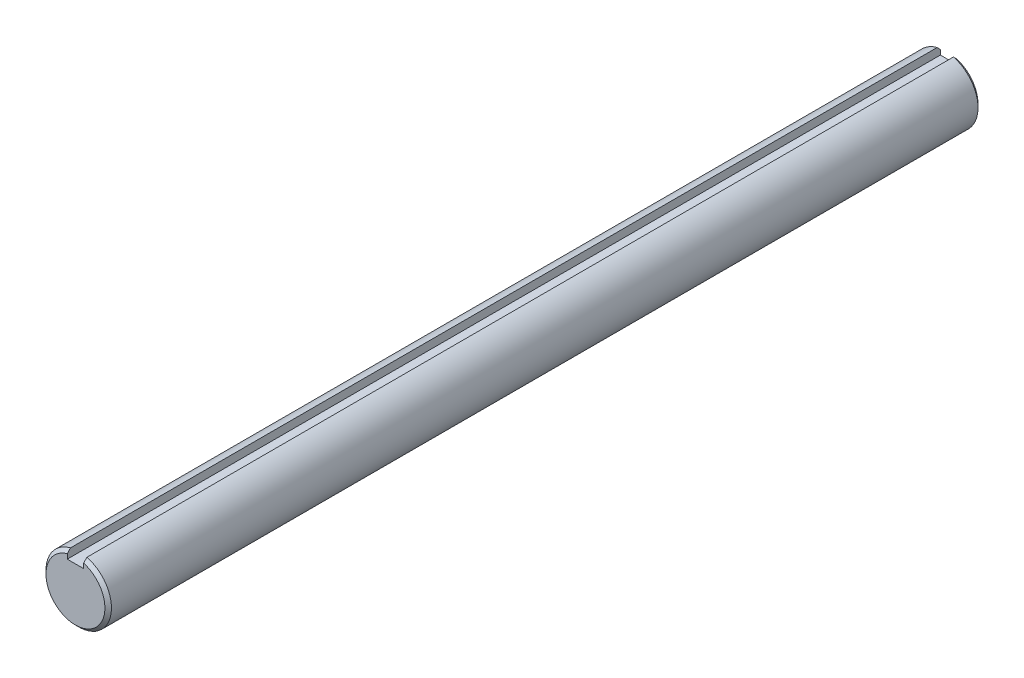
SolidWorks part; units mm, degrees
ref_plane "Front Plane" through (0, 0, 0) normal (0, 0, 1) x (1, 0, 0)
ref_plane "Top Plane" through (0, 0, 0) normal (0, 1, 0) x (1, 0, 0)
ref_plane "Right Plane" through (0, 0, 0) normal (1, 0, 0) x (0, 0, -1)
sketch "Sketch1" plane through (0, 0, 0) normal (0, 0, 1) x (1, 0, 0)
  line L0 (-6.7352, -6.7352) -> (-1.1225, -1.1225) construction
  line L1 (3.4925, 0) -> (-3.4925, 0) construction
  line L2 (0, 0) -> (0, 9.525) construction
  line L4 (-2.3813, 9.525) -> (2.3813, 9.525) construction
  line L5 (-2.3813, 9.525) -> (-2.3813, 6.8413) construction
  line L6 (-2.3813, 6.8413) -> (2.3813, 6.8413) construction
  line L7 (2.3813, 9.525) -> (2.3813, 6.8413) construction
  line L8 (-2.3813, 9.525) -> (2.3813, 6.8413) construction
  line L9 (-2.3813, 6.8413) -> (2.3813, 9.525) construction
  circle A0 centre (0, 0) radius 1.5875 construction
  circle A1 centre (0, 0) radius 9.525 construction
  point P6 (0, 8.1831)
  point P16 (-2.3813, 9.2225)
  dimension "Diameter" = 19.05
  dimension "Thread Dia" = 3.175
  dimension "D1" = 45
  dimension "Keyway Wd" = 4.7625
  dimension "Keyway Ht" = 2.3813
sketch "Sketch2" plane through (0, 0, 0) normal (1, 0, 0) x (0, 0, -1)
  line L0 (-127, -9.525) -> (127, -9.525) construction
  line L1 (0, 9.525) -> (0, -9.525) construction
  line L2 (0, 9.525) -> (0, -9.525) construction
  point P3 (88.9, -9.525)
  point P4 (-88.9, -9.525)
  dimension "Length" = 254
  dimension "D1" = 38.1
  dimension "D2" = 38.1
sketch "Sketch3" plane through (0, 0, 0) normal (0, 0, 1) x (1, 0, 0)
  circle A1 centre (0, 0) radius 9.525 construction
  circle A3 centre (0, 0) radius 9.525
extrude "Boss-Extrude2" add sketch "Sketch3" along normal up to vertex (127 mm away) and the other way up to vertex (127 mm away) up to point (0, -9.525, 127) other way up to point (0, -9.525, -127)
sketch "Sketch10" plane through (0, 0, 0) normal (0, 0, 1) x (1, 0, 0)
  line L1 (2.3813, 9.525) -> (2.3813, 6.8413) construction
  line L2 (-2.3813, 6.8413) -> (2.3813, 6.8413) construction
  line L3 (-2.3813, 9.525) -> (-2.3813, 6.8413) construction
  line L4 (-2.3813, 9.525) -> (2.3813, 9.525) construction
  line L5 (2.3813, 9.525) -> (2.3813, 6.8413)
  line L6 (-2.3813, 6.8413) -> (2.3813, 6.8413)
  line L7 (-2.3813, 9.525) -> (-2.3813, 6.8413)
  line L8 (-2.3813, 9.525) -> (2.3813, 9.525)
extrude "Cut-Extrude5" cut sketch "Sketch10" against normal through all both and the other way through all
chamfer "Chamfer1" distance 0.9525 angle 45 2 edges at (0, -9.525, 127) (0, -9.525, -127)
equation "\"D1@Chamfer1\"= \"Diameter@Sketch1\" / 20"
equation "\"D1@Sketch2\"=\"Diameter@Sketch1\"*2"
equation "\"D2@Sketch2\"=\"D1@Sketch2\""
